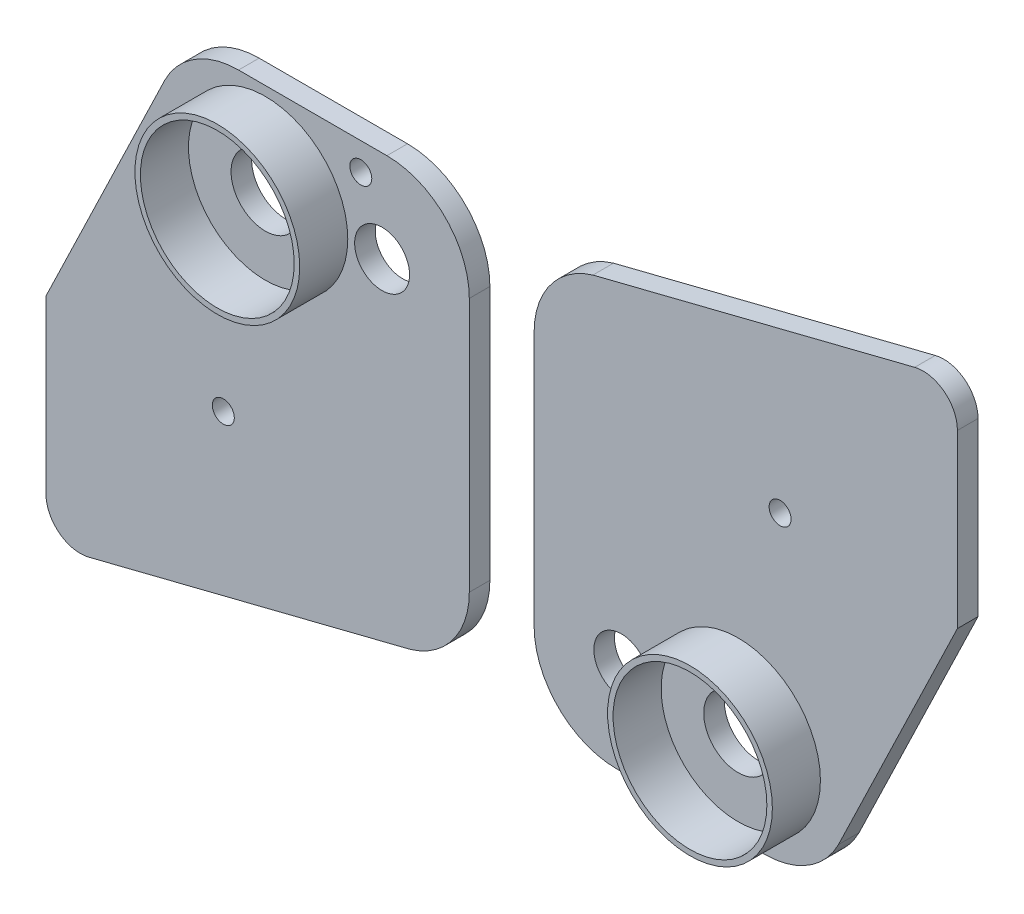
SolidWorks part; units mm, degrees
ref_plane "Ön Düzlem" through (0, 0, 0) normal (0, 0, 1) x (1, 0, 0)
ref_plane "Üst Düzlem" through (0, 0, 0) normal (0, 1, 0) x (1, 0, 0)
ref_plane "Sağ Düzlem" through (0, 0, 0) normal (1, 0, 0) x (0, 0, -1)
sketch "Model" plane through (0, 0, 0) normal (0, 0, 1) x (1, 0, 0)
  line L1 (294.6529, 168.1358) -> (294.6524, 143.1454)
  line L2 (356.3018, 168.1228) -> (356.3017, 161.5865)
  line L4 (356.3018, 168.1228) -> (356.3021, 198.6481)
  line L5 (344.3023, 210.6482) -> (322.6945, 210.6484)
  line L15 (300.8725, 138.2964) -> (347.7373, 150.089)
  line L16 (311.977, 204.0465) -> (294.6529, 168.1358)
  line L20 (421.1685, 222.3872) -> (374.3042, 210.5947)
  line L29 (365.7399, 199.0972) -> (365.7398, 195.8608)
  line L30 (365.7398, 192.5609) -> (365.7394, 162.0356)
  line L31 (410.0645, 156.6372) -> (427.3886, 192.5479)
  line L32 (377.7393, 150.0355) -> (399.3471, 150.0352)
  line L34 (427.3886, 192.5479) -> (427.3886, 217.5383)
  line L35 (365.7398, 195.8608) -> (365.7398, 192.5609)
  arc A0 (347.7373, 150.089) -> (356.3017, 161.5865) centre (344.3017, 161.5866) ccw
  arc A1 (294.6524, 143.1454) -> (300.8725, 138.2964) centre (299.6524, 143.1453) ccw
  arc A7 (356.3021, 198.6481) -> (344.3023, 210.6482) centre (344.3021, 198.6482) ccw
  arc A8 (322.6945, 210.6484) -> (311.977, 204.0465) centre (322.6943, 198.6484) ccw
  circle A9 centre (326.6017, 197.2779) radius 5
  circle A10 centre (343.6017, 197.2738) radius 4
  circle A11 centre (320.4767, 166.4735) radius 1.6
  arc A23 (374.3042, 210.5947) -> (365.7399, 199.0972) centre (377.7399, 199.0971) ccw
  arc A31 (427.3886, 217.5383) -> (421.1685, 222.3872) centre (422.3886, 217.5383) ccw
  circle A32 centre (395.4398, 163.4058) radius 5
  circle A33 centre (378.4398, 163.4099) radius 4
  circle A34 centre (401.5648, 194.2102) radius 1.6
  arc A38 (365.7394, 162.0356) -> (377.7393, 150.0355) centre (377.7394, 162.0355) ccw
  arc A39 (399.3471, 150.0352) -> (410.0645, 156.6372) centre (399.3472, 162.0352) ccw
  point P6 (277.2051, 160.202)
  dimension "D1" = 5
  dimension "D2" = 5
extrude "Yükseklik-Ekstrüzyon2" add sketch "Model" along normal blind 3
sketch "Çizim2" plane through (0, 0, 3) normal (0, 0, 1) x (1, 0, 0)
  circle A0 centre (395.4398, 163.4058) radius 11.2
  circle A1 centre (395.4398, 163.4058) radius 12
  circle A2 centre (326.6017, 197.2779) radius 11.2
  circle A3 centre (326.6017, 197.2779) radius 12
extrude "Yükseklik-Ekstrüzyon3" add sketch "Çizim2" along normal blind 7
sketch "Çizim3" plane through (0, 0, 3) normal (0, 0, 1) x (1, 0, 0)
  line L0 (344.3023, 210.6482) -> (322.6945, 210.6484) construction
  line L1 (333.4984, 210.6483) -> (333.4984, 163.4117) construction
  line L2 (388.5432, 150.0354) -> (388.5432, 206.6482) construction
  line L3 (377.7393, 150.0355) -> (399.3471, 150.0352) construction
  circle A0 centre (340.4984, 206.6482) radius 1.6
  circle A1 centre (381.5432, 154.0355) radius 1.6
  dimension "D1" = 4
  dimension "D3" = 4
  dimension "D2" = 7
  dimension "D4" = 7
extrude "Kes-Ekstrüzyon1" cut sketch "Çizim3" against normal blind 7
